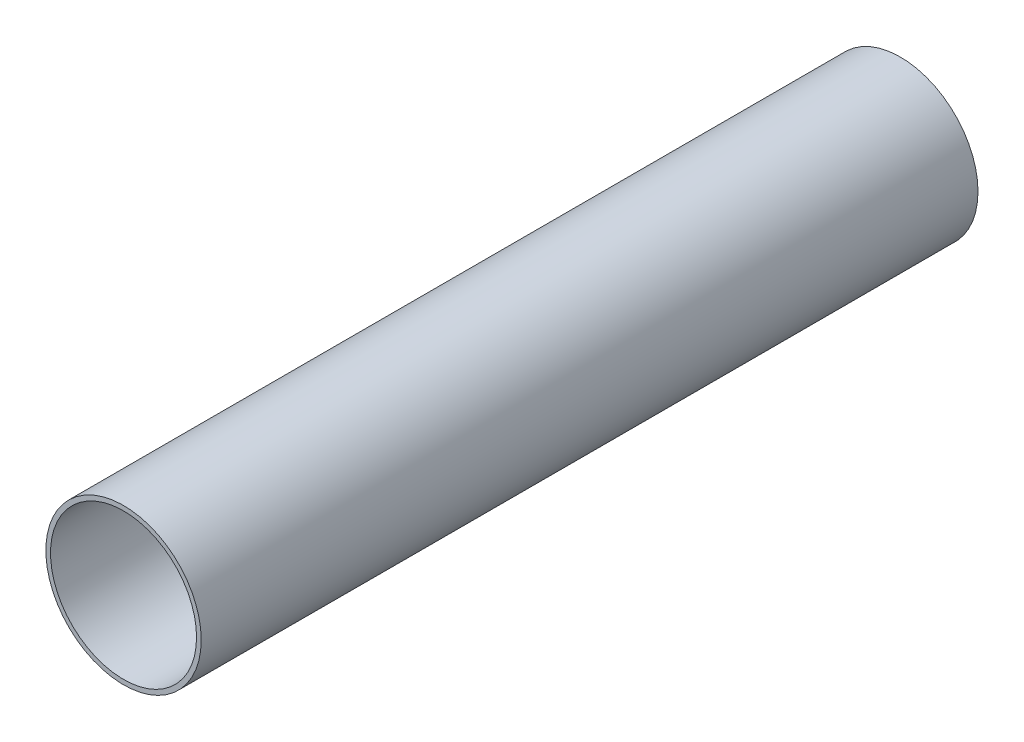
SolidWorks part; units mm, degrees
ref_plane "Front Plane" through (0, 0, 0) normal (0, 0, 1) x (1, 0, 0)
ref_plane "Top Plane" through (0, 0, 0) normal (0, 1, 0) x (1, 0, 0)
ref_plane "Right Plane" through (0, 0, 0) normal (1, 0, 0) x (0, 0, -1)
sketch "Sketch1" plane through (0, 0, 0) normal (0, 0, 1) x (1, 0, 0)
  circle A0 centre (0, 0) radius 50
  circle A1 centre (0, 0) radius 47
  dimension "D1" = 100
  dimension "D2" = 3
extrude "Boss-Extrude1" add sketch "Sketch1" along normal blind 500
sketch "Sketch2" plane through (0, 0, 0) normal (0, 1, 0) x (1, 0, 0)
  circle A0 centre (0, -130) radius 35
  circle A1 centre (0, -340) radius 35
  dimension "D1" = 70
  dimension "D4" = 70
  dimension "D2" = 130
  dimension "D3" = 210
extrude "Cut-Extrude1" cut sketch "Sketch2" against normal blind 500
